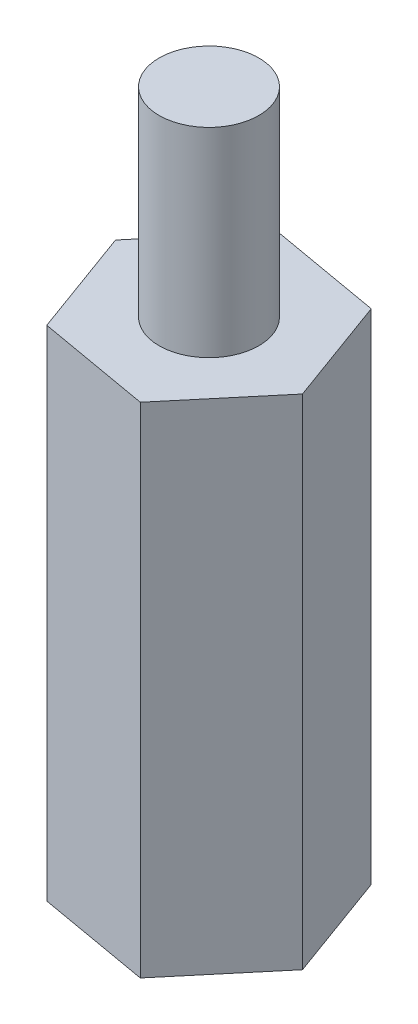
SolidWorks part; units mm, degrees
ref_plane "前视基准面" through (0, 0, 0) normal (0, 0, 1) x (1, 0, 0)
ref_plane "上视基准面" through (0, 0, 0) normal (0, 1, 0) x (1, 0, 0)
ref_plane "右视基准面" through (0, 0, 0) normal (1, 0, 0) x (0, 0, -1)
sketch "草图1" plane through (0, 0, 0) normal (0, 1, 0) x (1, 0, 0)
  line L1 (1.1872, -3.2543) -> (3.4119, -0.599)
  line L2 (3.4119, -0.599) -> (2.2247, 2.6553)
  line L3 (2.2247, 2.6553) -> (-1.1872, 3.2543)
  line L4 (-1.1872, 3.2543) -> (-3.4119, 0.599)
  line L5 (-3.4119, 0.599) -> (-2.2247, -2.6553)
  line L6 (-2.2247, -2.6553) -> (1.1872, -3.2543)
  circle A0 centre (0, 0) radius 3 construction
  dimension "D1" = 6
extrude "凸台-拉伸1" add sketch "草图1" along normal blind 15
sketch "草图2" plane through (0, 15, 0) normal (0, 1, 0) x (1, 0, 0)
  circle A0 centre (0, 0) radius 1.5
  dimension "D1" = 3
extrude "凸台-拉伸2" add sketch "草图2" along normal blind 6
